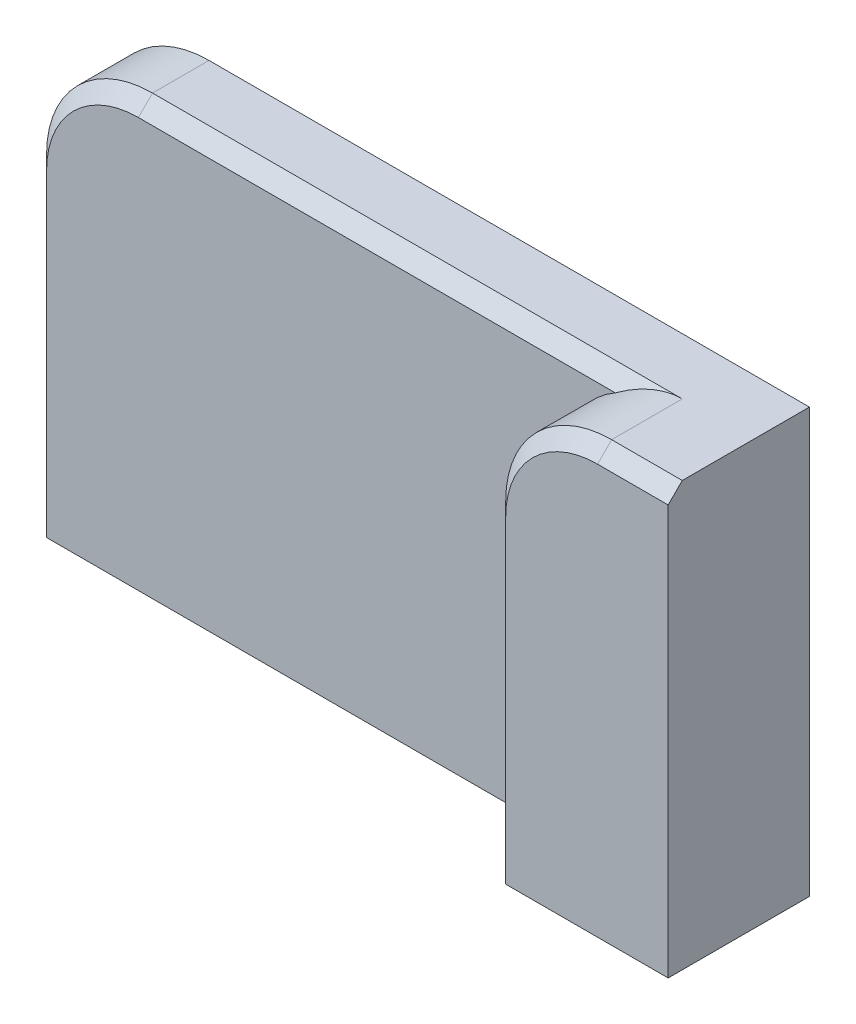
SolidWorks part; units mm, degrees
ref_plane "Front Plane" through (0, 0, 0) normal (0, 0, 1) x (1, 0, 0)
ref_plane "Top Plane" through (0, 0, 0) normal (0, 1, 0) x (1, 0, 0)
ref_plane "Right Plane" through (0, 0, 0) normal (1, 0, 0) x (0, 0, -1)
sketch "Sketch1" plane through (0, 0, 0) normal (0, 0, 1) x (1, 0, 0)
  line L1 (0, 0) -> (5, 0)
  line L2 (0, 0) -> (0, 3)
  line L3 (0, 3) -> (5, 3)
  line L4 (5, 0) -> (5, 3)
  dimension "D1" = 3
  dimension "D2" = 5
extrude "Boss-Extrude1" add sketch "Sketch1" along normal blind 0.5
sketch "Sketch2" plane through (0, 0, 0.5) normal (0, 0, 1) x (1, 0, 0)
  line L0 (5, 3) -> (0, 3) construction
  line L1 (5, 0) -> (3.75, 0)
  line L2 (5, 0) -> (5, 3)
  line L3 (5, 3) -> (3.75, 3)
  line L4 (3.75, 0) -> (3.75, 3)
  dimension "D1" = 1.25
extrude "Boss-Extrude3" add sketch "Sketch2" along normal blind 0.5
fillet "Fillet1" radius 0.75 2 edges at (3.75, 3, 0.75) (0, 3, 0.25)
chamfer "Chamfer1" distance 0.1 angle 45 6 edges at (2.625, 3, 0.5) (0.2197, 2.7803, 0.5) (0, 1.125, 0.5) (4.75, 3, 1) (3.9697, 2.7803, 1) (3.75, 1.125, 1)
